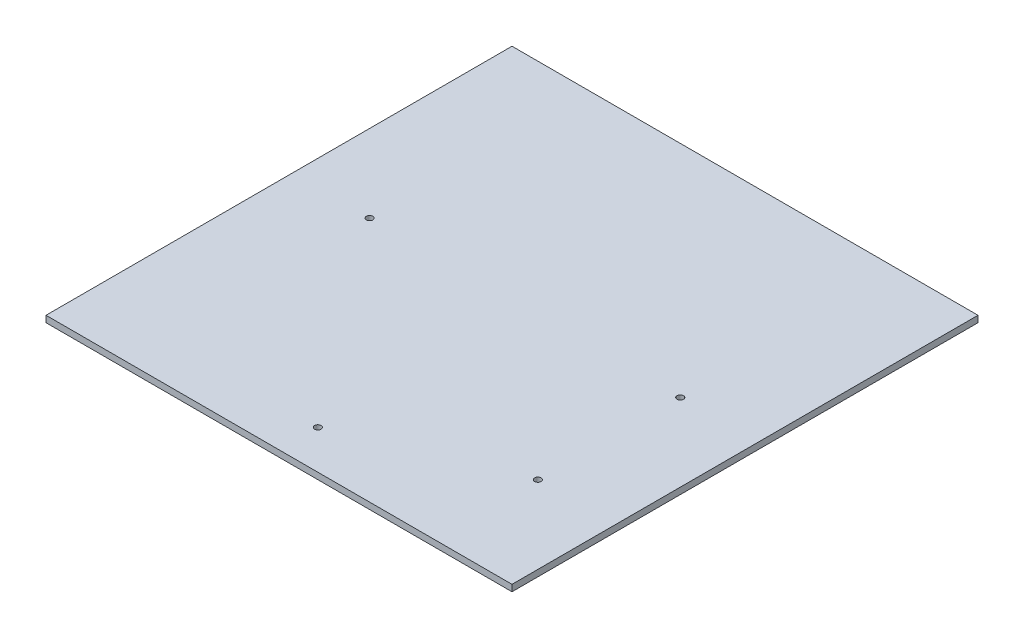
SolidWorks part; units mm, degrees
ref_plane "Front Plane" through (0, 0, 0) normal (0, 0, 1) x (1, 0, 0)
ref_plane "Top Plane" through (0, 0, 0) normal (0, 1, 0) x (1, 0, 0)
ref_plane "Right Plane" through (0, 0, 0) normal (1, 0, 0) x (0, 0, -1)
sketch "Sketch1" plane through (0, 0, 0) normal (0, 1, 0) x (1, 0, 0)
  line L1 (-457.2, -457.2) -> (457.2, -457.2)
  line L2 (-457.2, -457.2) -> (-457.2, 457.2)
  line L3 (-457.2, 457.2) -> (457.2, 457.2)
  line L4 (457.2, -457.2) -> (457.2, 457.2)
  line L5 (-457.2, -457.2) -> (457.2, 457.2) construction
  line L6 (-457.2, 457.2) -> (457.2, -457.2) construction
  point P0 (0, 0)
  dimension "D1" = 914.4
  dimension "D2" = 914.4
extrude "Base_Plate" add sketch "Sketch1" along normal blind 12.7
sketch "Sketch2" plane through (0, 12.7, 0) normal (0, 1, 0) x (1, 0, 0)
  line L0 (-457.2, -457.2) -> (457.2, -457.2) construction
  circle A0 centre (0, -381) radius 6.35
  circle A1 centre (304.8, -254) radius 6.35
  circle A2 centre (304.8, 25.4) radius 6.35
  circle A3 centre (-304.8, 25.4) radius 6.35
  point P0 (0, -381)
  dimension "D1" = 12.7
  dimension "D2" = 12.7
  dimension "D4" = 12.7
  dimension "D5" = 12.7
  dimension "D3" = 76.2
  dimension "D6" = 304.8
  dimension "D7" = 304.8
  dimension "D8" = 406.4
  dimension "D9" = 127
extrude "Center_Holes" cut sketch "Sketch2" against normal through all
